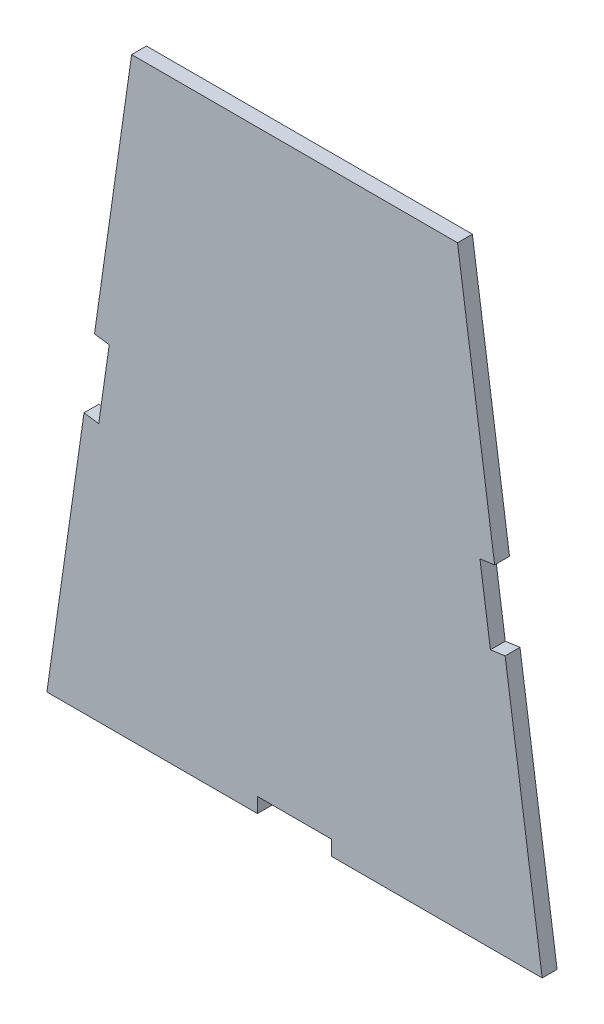
SolidWorks part; units mm, degrees
ref_plane "Front Plane" through (0, 0, 0) normal (0, 0, 1) x (1, 0, 0)
ref_plane "Top Plane" through (0, 0, 0) normal (0, 1, 0) x (1, 0, 0)
ref_plane "Right Plane" through (0, 0, 0) normal (1, 0, 0) x (0, 0, -1)
sketch "Sketch2" plane through (0, 0, 0) normal (0, 0, 1) x (1, 0, 0)
  line L73 (-142.1297, -86.5402) -> (-134.6376, -33.9651)
  line L74 (-42.1297, -86.5402) -> (-49.6219, -33.9651)
  line L75 (-59.2302, 33.4598) -> (-125.0293, 33.4598)
  line L76 (-142.1297, -86.5402) -> (-99.6297, -86.5402)
  line L77 (-84.6297, -86.5402) -> (-42.1297, -86.5402)
  line L78 (-99.6297, -83.5402) -> (-84.6297, -83.5402)
  line L79 (-84.6297, -83.5402) -> (-84.6297, -86.5402)
  line L80 (-99.6297, -83.5402) -> (-99.6297, -86.5402)
  line L82 (-51.738, -19.1152) -> (-59.2302, 33.4598)
  line L83 (-52.5919, -34.3884) -> (-54.708, -19.5384)
  line L84 (-54.708, -19.5384) -> (-51.738, -19.1152)
  line L86 (-49.6219, -33.9651) -> (-52.5919, -34.3884)
  line L87 (-134.6376, -33.9651) -> (-131.6676, -34.3884)
  line L88 (-129.5514, -19.5384) -> (-132.5214, -19.1152)
  line L89 (-131.6676, -34.3884) -> (-129.5514, -19.5384)
  line L90 (-132.5214, -19.1152) -> (-125.0293, 33.4598)
  point P37 (-92.1297, 33.4598)
  dimension "D2" = 81.89
  dimension "D3" = 81.89
  dimension "D4" = 15
  dimension "D5" = 3
  dimension "D6" = 15
  dimension "D7" = 3
  dimension "D11" = 100
extrude "Boss-Extrude1" add sketch "Sketch2" along normal blind 3
